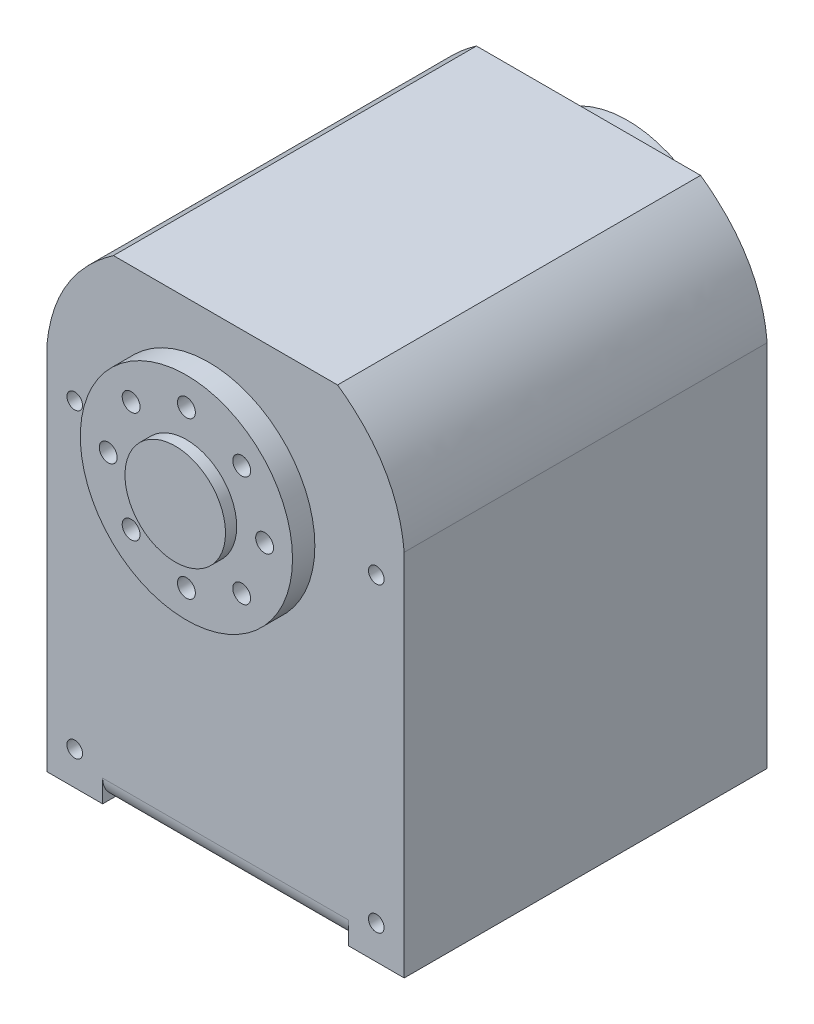
SolidWorks part; units mm, degrees
ref_plane "Plan de face" through (0, 0, 0) normal (0, 0, 1) x (1, 0, 0)
ref_plane "Plan de dessus" through (0, 0, 0) normal (0, 1, 0) x (1, 0, 0)
ref_plane "Plan de droite" through (0, 0, 0) normal (1, 0, 0) x (0, 0, -1)
sketch "Esquisse2" plane through (0, 0, 0) normal (0, 0, 1) x (1, 0, 0)
  line L1 (16, -21.5) -> (-16, -21.5)
  line L2 (16, -21.5) -> (16, 21.5)
  line L3 (16, 21.5) -> (-16, 21.5)
  line L4 (-16, -21.5) -> (-16, 21.5)
  line L5 (16, -21.5) -> (-16, 21.5) construction
  line L6 (16, 21.5) -> (-16, -21.5) construction
  point P0 (0, 0)
  dimension "D1" = 43
  dimension "D2" = 32
extrude "Boss.-Extru.1" add sketch "Esquisse2" along normal blind 32.5
sketch "Esquisse3" plane through (0, 0, 32.5) normal (0, 0, 1) x (1, 0, 0)
  line L0 (-16, -21.5) -> (16, -21.5) construction
  line L1 (-16, 21.5) -> (-16, -21.5) construction
  line L2 (0, 25.0625) -> (0, -26.6282) construction
  circle A0 centre (-13.5, -18.5) radius 0.7
  circle A1 centre (-13.5, 8.5) radius 0.7
  circle A2 centre (13.5, 8.5) radius 0.7
  circle A3 centre (13.5, -18.5) radius 0.7
  dimension "D1" = 1.4
  dimension "D4" = 1.4
  dimension "D2" = 3
  dimension "D3" = 2.5
  dimension "D5" = 30
extrude "Enlèv. mat.-Extru.1" cut sketch "Esquisse3" against normal through all
sketch "Esquisse4" plane through (0, 0, 32.5) normal (0, 0, 1) x (1, 0, 0)
  line L0 (-16, -21.5) -> (16, -21.5) construction
  circle A2 centre (0, 9.5) radius 4.5
  dimension "D1" = 31
  dimension "D4" = 9
extrude "Boss.-Extru.2" add sketch "Esquisse4" along normal blind 1.5 contours A2
sketch "Esquisse5" plane through (0, 0, 34) normal (0, 0, 1) x (1, 0, 0)
  line L0 (0, 9.5) -> (-28.3182, 9.5) construction
  line L1 (-16, -21.5) -> (16, -21.5) construction
  circle A0 centre (-2.7709, 1.3439) radius 0.0043
  circle A1 centre (0, 9.5) radius 9.5
  dimension "D1" = 19
  dimension "D2" = 31
extrude "Boss.-Extru.3" add sketch "Esquisse5" along normal blind 2
sketch "Esquisse6" plane through (0, 0, 36) normal (0, 0, 1) x (1, 0, 0)
  line L0 (0, 9.5) -> (-26.034, 9.5) construction
  circle A1 centre (-7, 9.5) radius 0.8
  circle A2 centre (-4.9497, 14.4497) radius 0.8
  circle A3 centre (0, 16.5) radius 0.8
  circle A4 centre (4.9497, 14.4497) radius 0.8
  circle A5 centre (7, 9.5) radius 0.8
  circle A6 centre (4.9497, 4.5503) radius 0.8
  circle A7 centre (0, 2.5) radius 0.8
  circle A8 centre (-4.9497, 4.5503) radius 0.8
  dimension "D1" = 1.6
  dimension "D2" = 7
  dimension "D3" = 8
extrude "Enlèv. mat.-Extru.2" cut sketch "Esquisse6" against normal blind 2
sketch "Esquisse7" plane through (0, 0, 36) normal (0, 0, 1) x (1, 0, 0)
  circle A1 centre (0, 9.5) radius 4.5
  circle A2 centre (0, 9.5) radius 4.5 construction
  dimension "D1" = 9
extrude "Boss.-Extru.4" add sketch "Esquisse7" along normal blind 1
sketch "Esquisse10" plane through (0, 0, 32.5) normal (0, 0, 1) x (1, 0, 0)
  line L0 (0, 24.8459) -> (0, -29.0218) construction
  line L3 (16, 21.5) -> (-16, 21.5) construction
  line L4 (-10.0321, 21.5) -> (10.0321, 21.5)
  line L5 (-16, 8.5) -> (-16, -18.5)
  line L6 (16, 8.5) -> (16, -18.5)
  line L7 (-16, -18.5) -> (-16, -21.5)
  line L8 (-16, -21.5) -> (16, -21.5)
  line L9 (16, -21.5) -> (16, -18.5)
  circle A0 centre (-13.5, -18.5) radius 2.5
  circle A1 centre (-13.5, 8.5) radius 2.5
  circle A2 centre (13.5, 8.5) radius 2.5
  circle A3 centre (13.5, -18.5) radius 2.5
  spline S0 degree 2 poles (-16, 8.5) (-16.6926, 16.8366) (-10.0321, 21.5) knots 0 0 0 1 1 1
  spline S1 degree 2 poles (16, 8.5) (16.6926, 16.8366) (10.0321, 21.5) knots 0 0 0 1 1 1
  point P24 (0, 21.5)
  line M6 (-16, 21.5) -> (-16, -21.5)
  line M8 (16, -21.5) -> (16, 21.5)
  line M9 (16, 21.5) -> (-16, 21.5)
  dimension "D1" = 5
  dimension "D2" = 5
extrude "Enlèv. mat.-Extru.4" cut sketch "Esquisse10" against normal through all contours S0 M6 M9 | S1 M8 M9
sketch "Esquisse14" plane through (-16, 0, 0) normal (-1, 0, 0) x (0, 0, 1)
  line L0 (0, -19.5) -> (0, -21.5)
  line L1 (0, -21.5) -> (2, -21.5)
  line L2 (32.5, -19.5) -> (32.5, -21.5)
  line L3 (32.5, -21.5) -> (30.5, -21.5)
  arc A0 (0, -19.5) -> (2, -21.5) centre (2, -19.5) ccw
  arc A1 (32.5, -19.5) -> (30.5, -21.5) centre (30.5, -19.5) cw
  dimension "D2" = 2
extrude "Enlèv. mat.-Extru.5" cut sketch "Esquisse14" against normal blind 22 from offset 5 offset against normal yes
ref_plane "Plan1" through (0, 0, 16.25) normal (0, 0, 1) x (1, 0, 0)
mirror "Symétrie1" about plane through (0, 0, 16.25) normal (0, 0, 1) of "Enlèv. mat.-Extru.2", "Boss.-Extru.4", "Boss.-Extru.3", "Boss.-Extru.2"
